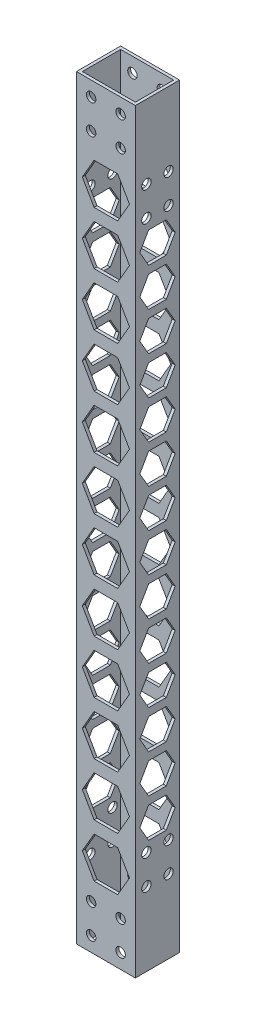
SolidWorks part; units mm, degrees
ref_plane "前视基准面" through (0, 0, 0) normal (0, 0, 1) x (1, 0, 0)
ref_plane "上视基准面" through (0, 0, 0) normal (0, 1, 0) x (1, 0, 0)
ref_plane "右视基准面" through (0, 0, 0) normal (1, 0, 0) x (0, 0, -1)
other "Configuration Table"
sketch "草图1" plane through (0, 0, 0) normal (0, 1, 0) x (1, 0, 0)
  line L5 (0, 0) -> (20, 0)
  line L6 (0, 0) -> (0, -15)
  line L11 (0, -15) -> (20, -15)
  line L12 (20, 0) -> (20, -15)
  line L13 (1, -1) -> (19, -1)
  line L14 (1, -1) -> (1, -14)
  line L15 (1, -14) -> (19, -14)
  line L16 (19, -1) -> (19, -14)
  dimension "D1" = 20
  dimension "D2" = 15
  dimension "D3" = 1
  dimension "D4" = 1
  dimension "D5" = 1
  dimension "D6" = 1
extrude "凸台-拉伸1" add sketch "草图1" along normal blind 256.4
sketch "草图2" plane through (0, 0, 15) normal (0, 0, 1) x (1, 0, 0)
  line L0 (20, 10) -> (0, 10) construction
  line L1 (20, 256.4) -> (20, 0) construction
  line L2 (0, 256.4) -> (0, 0) construction
  line L3 (10, 10) -> (10, 0) construction
  line L4 (0, 0) -> (20, 0) construction
  line L5 (20, 128.2) -> (0, 128.2) construction
  line L6 (10, 246.4) -> (10, 256.4) construction
  line L7 (20, 246.4) -> (0, 246.4) construction
  line L8 (10, 226.4) -> (10, 246.4) construction
  line L9 (14, 233.3282) -> (6, 233.3282)
  line L10 (6, 233.3282) -> (2, 226.4)
  line L11 (2, 226.4) -> (6, 219.4718)
  line L12 (6, 219.4718) -> (14, 219.4718)
  line L13 (14, 219.4718) -> (18, 226.4)
  line L14 (18, 226.4) -> (14, 233.3282)
  line L15 (18, 208.4) -> (14, 215.3282)
  line L16 (14, 201.4718) -> (18, 208.4)
  line L17 (6, 201.4718) -> (14, 201.4718)
  line L18 (2, 208.4) -> (6, 201.4718)
  line L19 (6, 215.3282) -> (2, 208.4)
  line L20 (14, 215.3282) -> (6, 215.3282)
  line L21 (18, 190.4) -> (14, 197.3282)
  line L22 (14, 183.4718) -> (18, 190.4)
  line L23 (6, 183.4718) -> (14, 183.4718)
  line L24 (2, 190.4) -> (6, 183.4718)
  line L25 (6, 197.3282) -> (2, 190.4)
  line L26 (14, 197.3282) -> (6, 197.3282)
  line L27 (18, 172.4) -> (14, 179.3282)
  line L28 (14, 165.4718) -> (18, 172.4)
  line L29 (6, 165.4718) -> (14, 165.4718)
  line L30 (2, 172.4) -> (6, 165.4718)
  line L31 (6, 179.3282) -> (2, 172.4)
  line L32 (14, 179.3282) -> (6, 179.3282)
  line L33 (18, 154.4) -> (14, 161.3282)
  line L34 (14, 147.4718) -> (18, 154.4)
  line L35 (6, 147.4718) -> (14, 147.4718)
  line L36 (2, 154.4) -> (6, 147.4718)
  line L37 (6, 161.3282) -> (2, 154.4)
  line L38 (14, 161.3282) -> (6, 161.3282)
  line L39 (18, 136.4) -> (14, 143.3282)
  line L40 (14, 129.4718) -> (18, 136.4)
  line L41 (6, 129.4718) -> (14, 129.4718)
  line L42 (2, 136.4) -> (6, 129.4718)
  line L43 (6, 143.3282) -> (2, 136.4)
  line L44 (14, 143.3282) -> (6, 143.3282)
  line L45 (18, 118.4) -> (14, 125.3282)
  line L46 (14, 111.4718) -> (18, 118.4)
  line L47 (6, 111.4718) -> (14, 111.4718)
  line L48 (2, 118.4) -> (6, 111.4718)
  line L49 (6, 125.3282) -> (2, 118.4)
  line L50 (14, 125.3282) -> (6, 125.3282)
  line L51 (18, 100.4) -> (14, 107.3282)
  line L52 (14, 93.4718) -> (18, 100.4)
  line L53 (6, 93.4718) -> (14, 93.4718)
  line L54 (2, 100.4) -> (6, 93.4718)
  line L55 (6, 107.3282) -> (2, 100.4)
  line L56 (14, 107.3282) -> (6, 107.3282)
  line L57 (18, 82.4) -> (14, 89.3282)
  line L58 (14, 75.4718) -> (18, 82.4)
  line L59 (6, 75.4718) -> (14, 75.4718)
  line L60 (2, 82.4) -> (6, 75.4718)
  line L61 (6, 89.3282) -> (2, 82.4)
  line L62 (14, 89.3282) -> (6, 89.3282)
  line L63 (18, 64.4) -> (14, 71.3282)
  line L64 (14, 57.4718) -> (18, 64.4)
  line L65 (6, 57.4718) -> (14, 57.4718)
  line L66 (2, 64.4) -> (6, 57.4718)
  line L67 (6, 71.3282) -> (2, 64.4)
  line L68 (14, 71.3282) -> (6, 71.3282)
  line L69 (18, 46.4) -> (14, 53.3282)
  line L70 (14, 39.4718) -> (18, 46.4)
  line L71 (6, 39.4718) -> (14, 39.4718)
  line L72 (2, 46.4) -> (6, 39.4718)
  line L73 (6, 53.3282) -> (2, 46.4)
  line L74 (14, 53.3282) -> (6, 53.3282)
  line L75 (18, 28.4) -> (14, 35.3282)
  line L76 (14, 21.4718) -> (18, 28.4)
  line L77 (6, 21.4718) -> (14, 21.4718)
  line L78 (2, 28.4) -> (6, 21.4718)
  line L79 (6, 35.3282) -> (2, 28.4)
  line L80 (14, 35.3282) -> (6, 35.3282)
  circle A0 centre (5, 5) radius 1.6
  circle A1 centre (15, 5) radius 1.6
  circle A2 centre (15, 15) radius 1.6
  circle A3 centre (5, 15) radius 1.6
  circle A4 centre (5, 241.4) radius 1.6
  circle A5 centre (15, 241.4) radius 1.6
  circle A6 centre (15, 251.4) radius 1.6
  circle A7 centre (5, 251.4) radius 1.6
  circle A8 centre (10, 226.4) radius 6.9282 construction
  circle A9 centre (10, 208.4) radius 6.9282 construction
  circle A10 centre (10, 190.4) radius 6.9282 construction
  circle A11 centre (10, 172.4) radius 6.9282 construction
  circle A12 centre (10, 154.4) radius 6.9282 construction
  circle A13 centre (10, 136.4) radius 6.9282 construction
  circle A14 centre (10, 118.4) radius 6.9282 construction
  circle A15 centre (10, 100.4) radius 6.9282 construction
  circle A16 centre (10, 82.4) radius 6.9282 construction
  circle A17 centre (10, 64.4) radius 6.9282 construction
  circle A18 centre (10, 46.4) radius 6.9282 construction
  circle A19 centre (10, 28.4) radius 6.9282 construction
  dimension "D2" = 3.2
  dimension "D1" = 10
  dimension "D3" = 5
  dimension "D4" = 5
  dimension "D5" = 8
  dimension "D6" = 20
  dimension "D8" = 18
  dimension "D7" = 12
extrude "切除-拉伸1" cut sketch "草图2" against normal through all
sketch "草图3" plane through (20, 0, 0) normal (1, 0, 0) x (0, 0, -1)
  line L0 (-15, 226.4) -> (0, 226.4) construction
  line L1 (-15, 256.4) -> (-15, 0) construction
  line L2 (0, 256.4) -> (0, 0) construction
  line L3 (-15, 256.4) -> (0, 256.4) construction
  line L4 (-7.5, 256.4) -> (-7.5, 226.4) construction
  line L5 (-15, 128.2) -> (0, 128.2) construction
  line L6 (-7.5, 0) -> (-7.5, 30) construction
  line L7 (-15, 30) -> (0, 30) construction
  line L8 (-7.5, 226.4) -> (-7.5, 212.4) construction
  line L9 (-4.5, 217.5962) -> (-10.5, 217.5962)
  line L10 (-10.5, 217.5962) -> (-13.5, 212.4)
  line L11 (-13.5, 212.4) -> (-10.5, 207.2038)
  line L12 (-10.5, 207.2038) -> (-4.5, 207.2038)
  line L13 (-4.5, 207.2038) -> (-1.5, 212.4)
  line L14 (-1.5, 212.4) -> (-4.5, 217.5962)
  line L15 (-4.5, 204.5962) -> (-10.5, 204.5962)
  line L16 (-4.5, 194.2038) -> (-1.5, 199.4)
  line L17 (-13.5, 199.4) -> (-10.5, 194.2038)
  line L18 (-10.5, 204.5962) -> (-13.5, 199.4)
  line L19 (-1.5, 199.4) -> (-4.5, 204.5962)
  line L20 (-10.5, 194.2038) -> (-4.5, 194.2038)
  line L21 (-4.5, 191.5962) -> (-10.5, 191.5962)
  line L22 (-4.5, 181.2038) -> (-1.5, 186.4)
  line L23 (-13.5, 186.4) -> (-10.5, 181.2038)
  line L24 (-10.5, 191.5962) -> (-13.5, 186.4)
  line L25 (-1.5, 186.4) -> (-4.5, 191.5962)
  line L26 (-10.5, 181.2038) -> (-4.5, 181.2038)
  line L27 (-4.5, 178.5962) -> (-10.5, 178.5962)
  line L28 (-4.5, 168.2038) -> (-1.5, 173.4)
  line L29 (-13.5, 173.4) -> (-10.5, 168.2038)
  line L30 (-10.5, 178.5962) -> (-13.5, 173.4)
  line L31 (-1.5, 173.4) -> (-4.5, 178.5962)
  line L32 (-10.5, 168.2038) -> (-4.5, 168.2038)
  line L33 (-4.5, 165.5962) -> (-10.5, 165.5962)
  line L34 (-4.5, 155.2038) -> (-1.5, 160.4)
  line L35 (-13.5, 160.4) -> (-10.5, 155.2038)
  line L36 (-10.5, 165.5962) -> (-13.5, 160.4)
  line L37 (-1.5, 160.4) -> (-4.5, 165.5962)
  line L38 (-10.5, 155.2038) -> (-4.5, 155.2038)
  line L39 (-4.5, 152.5962) -> (-10.5, 152.5962)
  line L40 (-4.5, 142.2038) -> (-1.5, 147.4)
  line L41 (-13.5, 147.4) -> (-10.5, 142.2038)
  line L42 (-10.5, 152.5962) -> (-13.5, 147.4)
  line L43 (-1.5, 147.4) -> (-4.5, 152.5962)
  line L44 (-10.5, 142.2038) -> (-4.5, 142.2038)
  line L45 (-4.5, 139.5962) -> (-10.5, 139.5962)
  line L46 (-4.5, 129.2038) -> (-1.5, 134.4)
  line L47 (-13.5, 134.4) -> (-10.5, 129.2038)
  line L48 (-10.5, 139.5962) -> (-13.5, 134.4)
  line L49 (-1.5, 134.4) -> (-4.5, 139.5962)
  line L50 (-10.5, 129.2038) -> (-4.5, 129.2038)
  line L51 (-4.5, 126.5962) -> (-10.5, 126.5962)
  line L52 (-4.5, 116.2038) -> (-1.5, 121.4)
  line L53 (-13.5, 121.4) -> (-10.5, 116.2038)
  line L54 (-10.5, 126.5962) -> (-13.5, 121.4)
  line L55 (-1.5, 121.4) -> (-4.5, 126.5962)
  line L56 (-10.5, 116.2038) -> (-4.5, 116.2038)
  line L57 (-4.5, 113.5962) -> (-10.5, 113.5962)
  line L58 (-4.5, 103.2038) -> (-1.5, 108.4)
  line L59 (-13.5, 108.4) -> (-10.5, 103.2038)
  line L60 (-10.5, 113.5962) -> (-13.5, 108.4)
  line L61 (-1.5, 108.4) -> (-4.5, 113.5962)
  line L62 (-10.5, 103.2038) -> (-4.5, 103.2038)
  line L63 (-4.5, 100.5962) -> (-10.5, 100.5962)
  line L64 (-4.5, 90.2038) -> (-1.5, 95.4)
  line L65 (-13.5, 95.4) -> (-10.5, 90.2038)
  line L66 (-10.5, 100.5962) -> (-13.5, 95.4)
  line L67 (-1.5, 95.4) -> (-4.5, 100.5962)
  line L68 (-10.5, 90.2038) -> (-4.5, 90.2038)
  line L69 (-4.5, 87.5962) -> (-10.5, 87.5962)
  line L70 (-4.5, 77.2038) -> (-1.5, 82.4)
  line L71 (-13.5, 82.4) -> (-10.5, 77.2038)
  line L72 (-10.5, 87.5962) -> (-13.5, 82.4)
  line L73 (-1.5, 82.4) -> (-4.5, 87.5962)
  line L74 (-10.5, 77.2038) -> (-4.5, 77.2038)
  line L75 (-4.5, 74.5962) -> (-10.5, 74.5962)
  line L76 (-4.5, 64.2038) -> (-1.5, 69.4)
  line L77 (-13.5, 69.4) -> (-10.5, 64.2038)
  line L78 (-10.5, 74.5962) -> (-13.5, 69.4)
  line L79 (-1.5, 69.4) -> (-4.5, 74.5962)
  line L80 (-10.5, 64.2038) -> (-4.5, 64.2038)
  line L81 (-4.5, 61.5962) -> (-10.5, 61.5962)
  line L82 (-4.5, 51.2038) -> (-1.5, 56.4)
  line L83 (-13.5, 56.4) -> (-10.5, 51.2038)
  line L84 (-10.5, 61.5962) -> (-13.5, 56.4)
  line L85 (-1.5, 56.4) -> (-4.5, 61.5962)
  line L86 (-10.5, 51.2038) -> (-4.5, 51.2038)
  line L87 (-4.5, 48.5962) -> (-10.5, 48.5962)
  line L88 (-4.5, 38.2038) -> (-1.5, 43.4)
  line L89 (-13.5, 43.4) -> (-10.5, 38.2038)
  line L90 (-10.5, 48.5962) -> (-13.5, 43.4)
  line L91 (-1.5, 43.4) -> (-4.5, 48.5962)
  line L92 (-10.5, 38.2038) -> (-4.5, 38.2038)
  circle A0 centre (-11.25, 231.4) radius 1.6
  circle A1 centre (-3.75, 231.4) radius 1.6
  circle A2 centre (-3.75, 221.4) radius 1.6
  circle A3 centre (-11.25, 221.4) radius 1.6
  circle A4 centre (-11.25, 35) radius 1.6
  circle A5 centre (-3.75, 35) radius 1.6
  circle A6 centre (-3.75, 25) radius 1.6
  circle A7 centre (-11.25, 25) radius 1.6
  circle A8 centre (-7.5, 212.4) radius 5.1962 construction
  circle A9 centre (-7.5, 199.4) radius 5.1962 construction
  circle A10 centre (-7.5, 186.4) radius 5.1962 construction
  circle A11 centre (-7.5, 173.4) radius 5.1962 construction
  circle A12 centre (-7.5, 160.4) radius 5.1962 construction
  circle A13 centre (-7.5, 147.4) radius 5.1962 construction
  circle A14 centre (-7.5, 134.4) radius 5.1962 construction
  circle A15 centre (-7.5, 121.4) radius 5.1962 construction
  circle A16 centre (-7.5, 108.4) radius 5.1962 construction
  circle A17 centre (-7.5, 95.4) radius 5.1962 construction
  circle A18 centre (-7.5, 82.4) radius 5.1962 construction
  circle A19 centre (-7.5, 69.4) radius 5.1962 construction
  circle A20 centre (-7.5, 56.4) radius 5.1962 construction
  circle A21 centre (-7.5, 43.4) radius 5.1962 construction
  dimension "D2" = 3.2
  dimension "D1" = 30
  dimension "D3" = 3.75
  dimension "D4" = 5
  dimension "D5" = 14
  dimension "D6" = 6
  dimension "D8" = 13
  dimension "D7" = 14
extrude "切除-拉伸2" cut sketch "草图3" against normal through all
